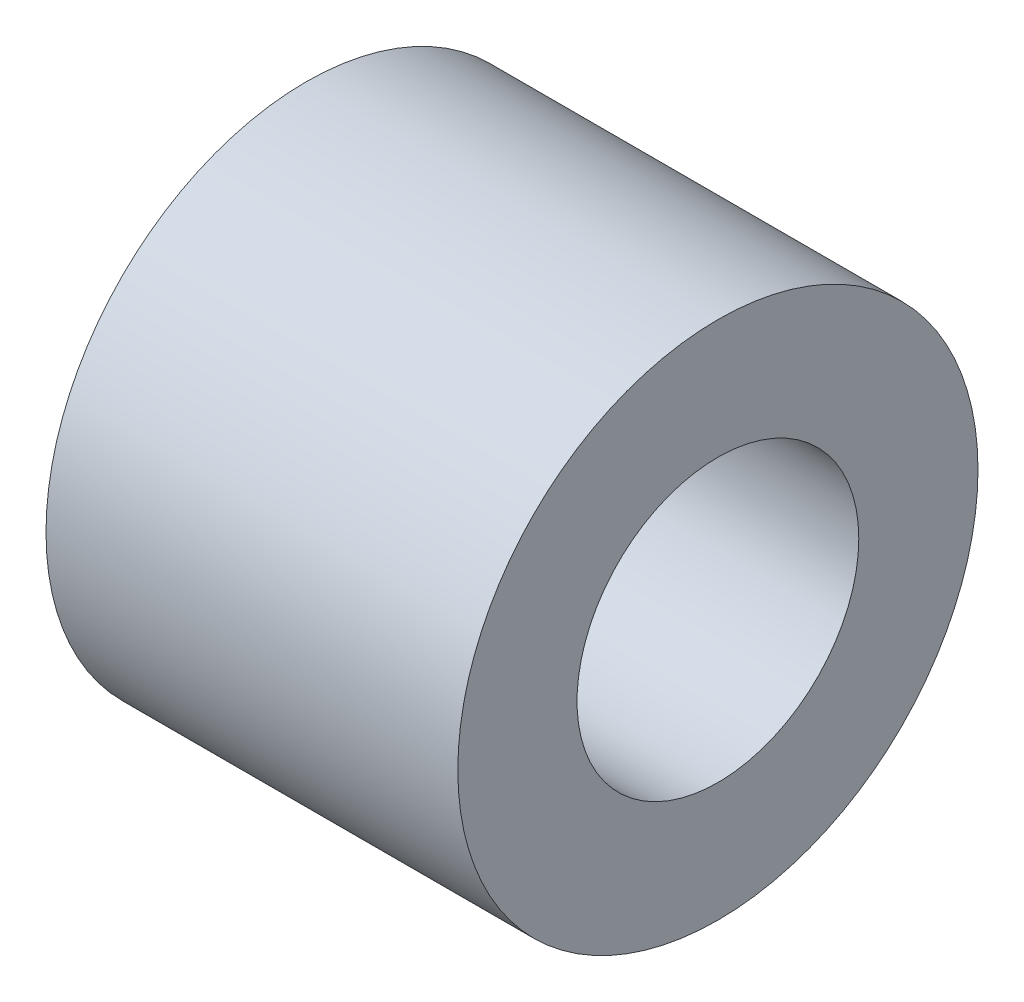
SolidWorks part; units mm, degrees
ref_plane "Front Plane" through (0, 0, 0) normal (0, 0, 1) x (1, 0, 0)
ref_plane "Top Plane" through (0, 0, 0) normal (0, 1, 0) x (1, 0, 0)
ref_plane "Right Plane" through (0, 0, 0) normal (1, 0, 0) x (0, 0, -1)
sketch "Sketch1" plane through (0, 0, 0) normal (1, 0, 0) x (0, 0, -1)
  circle A0 centre (0, 0) radius 2.4
  dimension "D1" = 4.8
extrude "Boss-Extrude1" add sketch "Sketch1" along normal blind 3.8
sketch "Sketch2" plane through (3.8, 0, 0) normal (1, 0, 0) x (0, 0, -1)
  circle A0 centre (0, 0) radius 1.3
  dimension "D1" = 2.6
extrude "Cut-Extrude1" cut sketch "Sketch2" against normal blind 3.8
